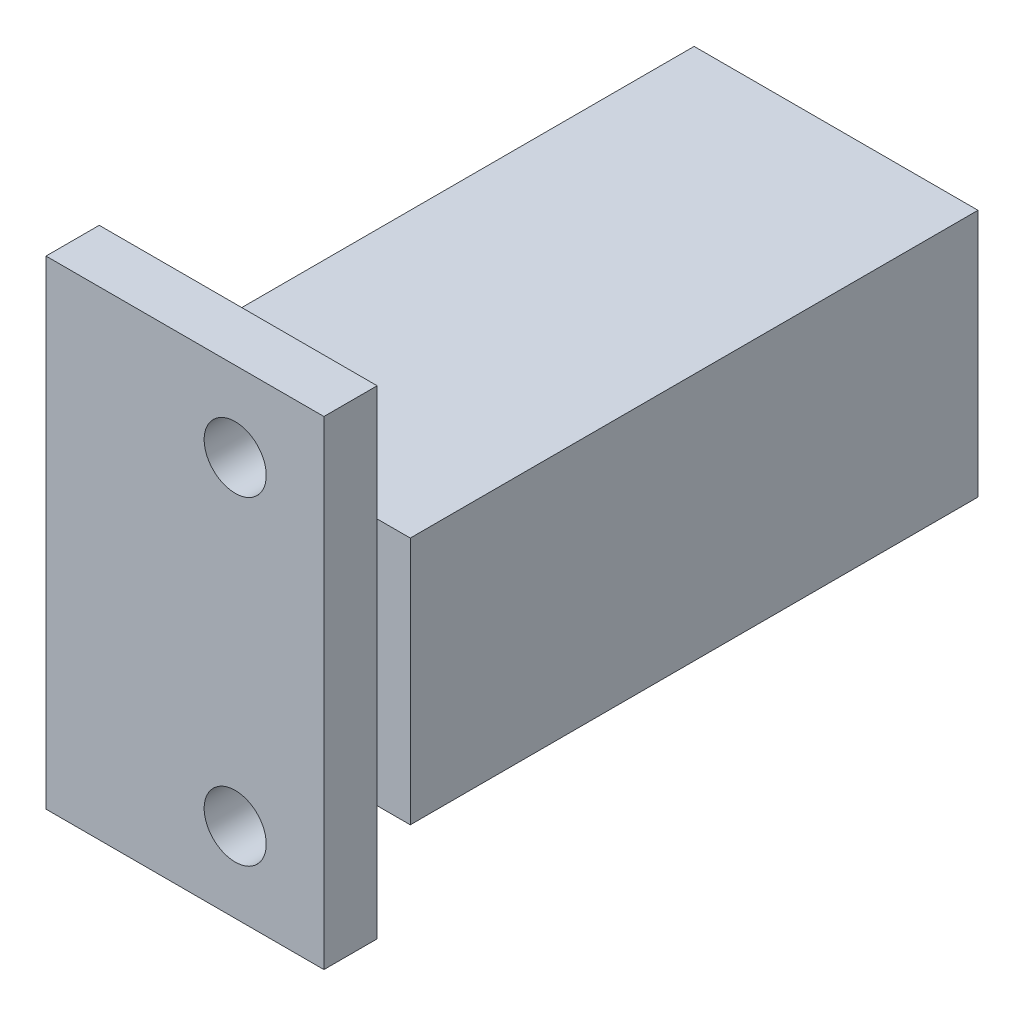
SolidWorks part; units mm, degrees
ref_plane "Front Plane" through (0, 0, 0) normal (1, 0, 0) x (0, 1, 0)
ref_plane "Top Plane" through (0, 0, 0) normal (0, 0, 1) x (0, 1, 0)
ref_plane "Right Plane" through (0, 0, 0) normal (0, 1, 0) x (-1, 0, 0)
sketch "Sketch1" plane through (0, 0, 0) normal (1, 0, 0) x (0, 1, 0)
  line L0 (0, -9.6429) -> (0, 9.6429) construction
  line L1 (-13.5, 8) -> (13.5, 8) construction
  line L2 (-13.5, 8) -> (-13.5, -8)
  line L3 (-13.5, -8) -> (13.5, -8)
  line L4 (13.5, 8) -> (13.5, -8)
  line L5 (-13.5, 8) -> (13.5, -8) construction
  line L6 (-13.5, -8) -> (13.5, 8) construction
  line L7 (-5, 58) -> (5, 58)
  line L8 (-5, 58) -> (-5, 8)
  line L9 (-5, 8) -> (5, 8) construction
  line L10 (5, 58) -> (5, 8)
  line L11 (-5, 58) -> (5, 8) construction
  line L12 (-5, 8) -> (5, 58) construction
  line L13 (-13.5, 8) -> (-5, 8)
  line L14 (5, 8) -> (13.5, 8)
  point P0 (0, 0)
  point P6 (0, 33)
  dimension "D1" = 10
  dimension "D2" = 16
  dimension "D3" = 27
  dimension "D4" = 50
extrude "Boss-Extrude1" add sketch "Sketch1" against normal blind 1.5
sketch "Sketch2" plane through (0, 0, 0) normal (1, 0, 0) x (0, 1, 0)
  line L0 (-13.5, -8) -> (13.5, -8) construction
  line L1 (-7, -8) -> (7, -8)
  line L2 (-7, -8) -> (-7, -40)
  line L3 (-7, -40) -> (7, -40)
  line L4 (7, -8) -> (7, -40)
  line L5 (13.5, 8) -> (5, 8) construction
  line L6 (0, -9.6429) -> (0, 9.6429) construction
  point P8 (0, -8)
  dimension "D1" = 14
  dimension "D2" = 48
extrude "Boss-Extrude2" add sketch "Sketch2" along normal blind 16 separate body
sketch "Sketch3" plane through (0, 0, -8) normal (0, 0, 1) x (1, 0, 0)
  line L0 (-1.5, 13.5) -> (0, 13.5) construction
  line L1 (14.1323, -13.5) -> (-1.5325, -13.5)
  line L2 (14.1323, -13.5) -> (14.1323, 13.5)
  line L3 (14.1323, 13.5) -> (-1.5325, 13.5)
  line L4 (-1.5325, -13.5) -> (-1.5325, 13.5)
  line L5 (-1.5, -13.5) -> (0, -13.5) construction
  line L6 (9.1323, 9) -> (9.1323, -9) construction
  line L7 (9.625, 0) -> (-9.625, 0) construction
  circle A0 centre (9.1323, 9) radius 1.75
  circle A1 centre (9.1323, -9) radius 1.75
  dimension "D1" = 3.5
  dimension "D2" = 3.5
  dimension "D4" = 18
  dimension "D3" = 5
  dimension "D5" = 9
extrude "Boss-Extrude3" add sketch "Sketch3" along normal blind 3 and the other way blind 0.001
sketch "Sketch5" plane through (0, 0, -40) normal (0, 0, -1) x (1, 0, 0)
  line L0 (-9.6429, 0) -> (9.6429, 0) construction
  line L1 (2, -7) -> (16, 7) construction
  circle A0 centre (9, 0) radius 2.5
  point P8 (9, 0)
  dimension "D1" = 5
extrude "Boss-Extrude4" add sketch "Sketch5" along normal blind 4 draft 15 contours A0
sketch "Sketch6" plane through (0, 0, 0) normal (1, 0, 0) x (0, 1, 0)
  line L0 (-1.1947, 48) -> (-1.1947, 18) construction
  line L1 (-5, 8) -> (-13.5, 8) construction
  line L3 (0.5553, 48) -> (0.5553, 18)
  line L4 (-2.9447, 48) -> (-2.9447, 18)
  arc A0 (-2.9447, 18) -> (0.5553, 18) centre (-1.1947, 18) ccw
  arc A1 (0.5553, 48) -> (-2.9447, 48) centre (-1.1947, 48) ccw
  dimension "D2" = 3.5
  dimension "D3" = 3.5
  dimension "D1" = 30
  dimension "D4" = 10
extrude "Cut-Extrude1" cut sketch "Sketch6" against normal blind 10
sketch "Sketch7" plane through (14.1323, 0, 0) normal (1, 0, 0) x (0, 1, 0)
  line L1 (-35.4541, 65.2779) -> (35.6117, 65.2779)
  line L2 (-35.4541, 65.2779) -> (-35.4541, -5)
  line L3 (-35.4541, -5) -> (35.6117, -5)
  line L4 (35.6117, 65.2779) -> (35.6117, -5)
  line L5 (13.5, -5) -> (-13.5, -5) construction
  point P4 (35.6117, -3.6362)
extrude "Cut-Extrude2" cut sketch "Sketch7" against normal blind 30
